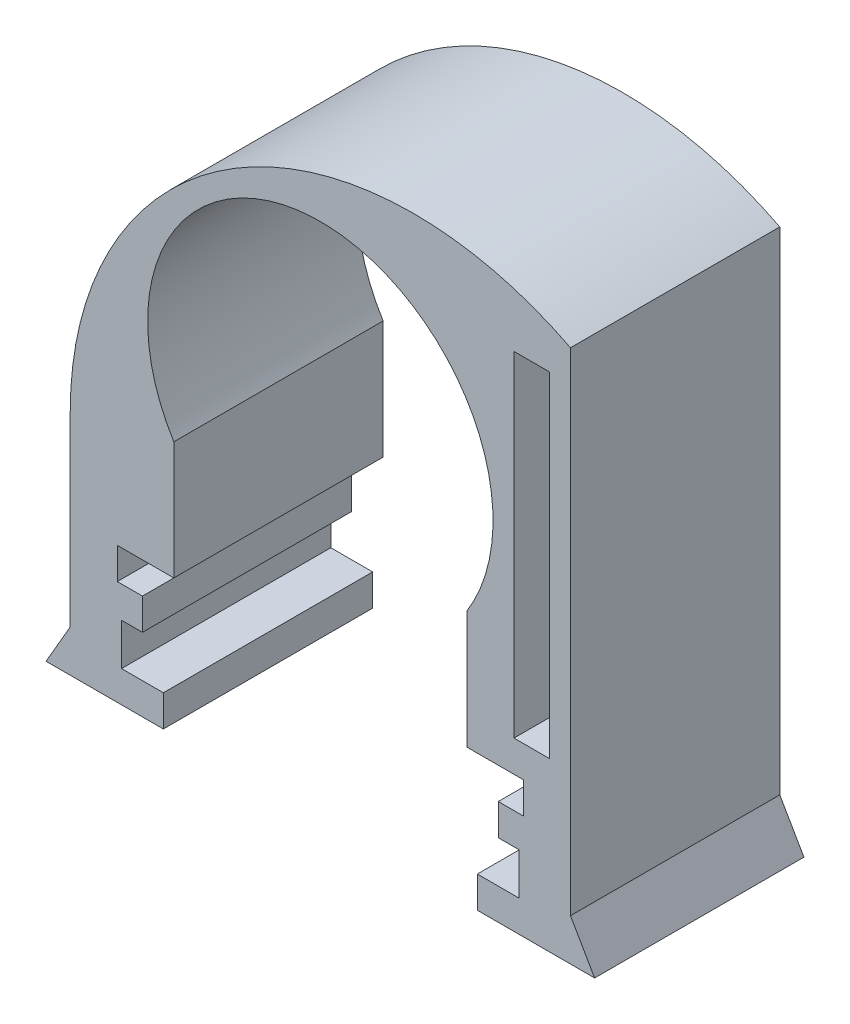
SolidWorks part; units mm, degrees
ref_plane "Front Plane" through (0, 0, 0) normal (0, 0, 1) x (1, 0, 0)
ref_plane "Top Plane" through (0, 0, 0) normal (0, 1, 0) x (1, 0, 0)
ref_plane "Right Plane" through (0, 0, 0) normal (1, 0, 0) x (0, 0, -1)
sketch "Sketch1" plane through (0, 0, 0) normal (0, 0, 1) x (1, 0, 0)
  line L0 (8.5, -13) -> (9.5, -13)
  line L1 (9.5, -13) -> (9.5, -15)
  line L2 (9.5, -15) -> (7.5, -15)
  line L3 (7.5, -15) -> (7.5, -16.5)
  line L4 (7.5, -16.5) -> (13.1047, -16.5)
  line L5 (13.1047, -16.5) -> (11.95, -14.5)
  line L6 (11.95, -14.5) -> (11.95, 9)
  line L7 (8.5, -13) -> (8.5, -11.5)
  line L8 (8.5, -11.5) -> (9.7, -11.5)
  line L9 (9.7, -11.5) -> (9.7, -10)
  line L10 (9.7, -10) -> (7, -10)
  line L11 (7, -10) -> (7, -4.3661)
  line L12 (0, 0) -> (0, -18.146) construction
  line L13 (-13.1047, -16.5) -> (-11.95, -14.5)
  line L14 (-11.95, -14.5) -> (-11.95, -5.6014)
  line L15 (-8.5, -11.5) -> (-9.7, -11.5)
  line L16 (-8.5, -13) -> (-8.5, -11.5)
  line L17 (-7.5, -16.5) -> (-13.1047, -16.5)
  line L18 (-7.5, -15) -> (-7.5, -16.5)
  line L19 (-9.5, -15) -> (-7.5, -15)
  line L20 (-9.5, -13) -> (-9.5, -15)
  line L21 (-8.5, -13) -> (-9.5, -13)
  line L22 (-9.7, -11.5) -> (-9.7, -10)
  line L23 (-9.7, -10) -> (-7, -10)
  line L24 (-7, -10) -> (-7, -4.3661)
  line L26 (9.25, 7.5) -> (10.95, 7.5)
  line L27 (9.25, 7.5) -> (9.25, -8.5)
  line L28 (9.25, -8.5) -> (10.95, -8.5)
  line L29 (10.95, 7.5) -> (10.95, -8.5)
  arc A0 (7, -4.3661) -> (-7, -4.3661) centre (0, 0) ccw
  arc A1 (11.95, 9) -> (-11.95, -5.6014) centre (4.4603, -5.6014) ccw
  dimension "D5" = 1.5
  dimension "D10" = 2
  dimension "D1" = 16.5
  dimension "D6" = 1
  dimension "D20" = 1
  dimension "D2" = 16
  dimension "D3" = 1.7
  dimension "D4" = 1.5
  dimension "D7" = 19.4
  dimension "D8" = 19
  dimension "D9" = 1.5
  dimension "D11" = 2
  dimension "D12" = 1
  dimension "D13" = 10
  dimension "D14" = 1.5
  dimension "D15" = 2
  dimension "D16" = 60
  dimension "D17" = 1
  dimension "D18" = 14
  dimension "D19" = 1.5
extrude "Boss-Extrude1" add sketch "Sketch1" along normal blind 10
